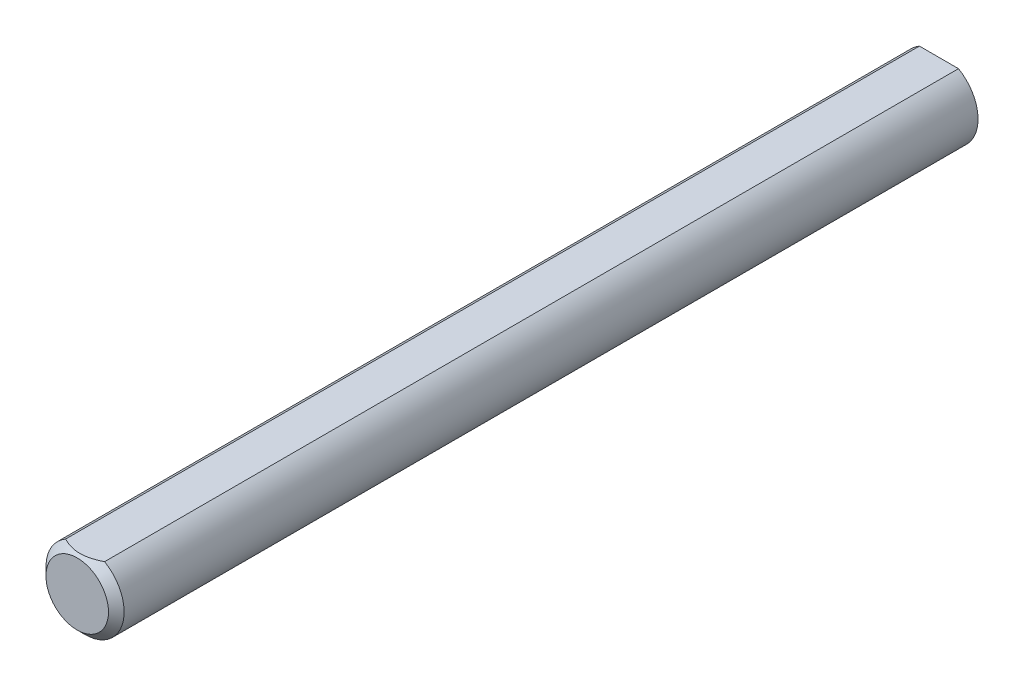
SolidWorks part; units mm, degrees
ref_plane "Front" through (0, 0, 0) normal (0, 0, 1) x (1, 0, 0)
ref_plane "Top" through (0, 0, 0) normal (0, 1, 0) x (1, 0, 0)
ref_plane "Right" through (0, 0, 0) normal (1, 0, 0) x (0, 0, -1)
sketch "Sketch1" plane through (0, 0, 0) normal (0, 0, 1) x (1, 0, 0)
  circle A0 centre (0, 0) radius 3.175
  dimension "D1" = 6.35
extrude "Extrude1" add sketch "Sketch1" along normal mid plane 152.4
chamfer "Chamfer1" distance 0.635 angle 45 2 edges at (3.175, 0, -76.2) (3.175, 0, 76.2)
sketch "Sketch13" plane through (0, 0, 0) normal (0, 0, 1) x (1, 0, 0)
  line L3 (-1.5875, 2.7496) -> (1.5875, 2.7496)
  circle A0 centre (0, 0) radius 3.175 construction
  arc A1 (1.5875, 2.7496) -> (-1.5875, 2.7496) centre (0, 0) ccw
  dimension "D1" = 3.175
extrude "Extrude7" cut sketch "Sketch13" against normal through all and the other way through all
sketch "Sketch14" plane through (0, 0, -76.2) normal (0, 0, -1) x (-1, 0, 0)
  circle A0 centre (0, 0) radius 3.175
  arc A1 (-1.5875, 2.7496) -> (1.5875, 2.7496) centre (0, 0) ccw construction
extrude "Cut-Extrude1" cut sketch "Sketch14" against normal blind 82.4
equation "\"D1@Chamfer1\" = \"D1@Sketch1\" * .1"
equation "\"D1@Sketch13\" = \"D1@Sketch1\" * .5"
